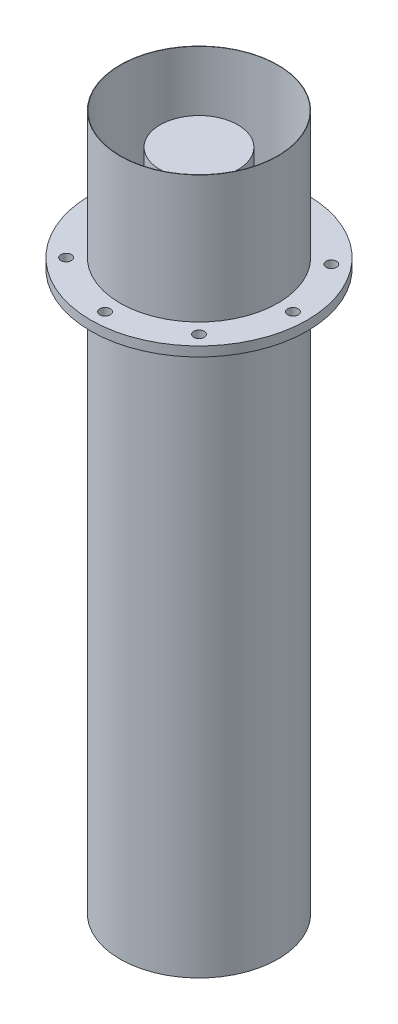
SolidWorks part; units mm, degrees
ref_plane "Alzado" through (0, 0, 0) normal (0, 0, 1) x (1, 0, 0)
ref_plane "Planta" through (0, 0, 0) normal (0, 1, 0) x (1, 0, 0)
ref_plane "Vista lateral" through (0, 0, 0) normal (1, 0, 0) x (0, 0, -1)
sketch "Croquis1" plane through (0, 0, 0) normal (0, 1, 0) x (1, 0, 0)
  circle A0 centre (0, 0) radius 24.8
  dimension "D1" = 49.6
extrude "Saliente-Extruir1" add sketch "Croquis1" along normal blind 218.4
sketch "Croquis2" plane through (0, 0, 0) normal (0, -1, 0) x (1, 0, 0)
  line L0 (0, 0) -> (0, 1.5) construction
  line L1 (0, 1.5) -> (1.4697, 1.5)
  line L2 (0, 1.5) -> (-1.4697, 1.5)
  arc A0 (-1.4697, 1.5) -> (1.4697, 1.5) centre (0, 0) ccw
  dimension "D1" = 4.2
  dimension "D2" = 1.5
extrude "Cortar-Extruir1" cut sketch "Croquis2" against normal blind 10
sketch "Croquis3" plane through (0, 218.4, 0) normal (0, 1, 0) x (1, 0, 0)
  circle A0 centre (0, 0) radius 12.2
  dimension "D1" = 24.4
extrude "Saliente-Extruir2" add sketch "Croquis3" along normal blind 30
sketch "Croquis4" plane through (0, 0, 0) normal (0, -1, 0) x (1, 0, 0)
  line L0 (0, 0) -> (0, 6.3) construction
  line L1 (0, 6.3) -> (-3.7858, 6.3) construction
  line L2 (0, 0) -> (-17.7679, 0) construction
  line L3 (-7.35, 0) -> (-3.7858, 6.3) construction
  line L5 (3.5475, 6.2184) -> (-3.6116, 6.1814)
  line L6 (-3.6116, 6.1814) -> (-7.159, -0.037)
  line L7 (-7.159, -0.037) -> (-3.5475, -6.2184)
  line L8 (-3.5475, -6.2184) -> (3.6116, -6.1814)
  line L9 (3.6116, -6.1814) -> (7.159, 0.037)
  line L10 (7.159, 0.037) -> (3.5475, 6.2184)
  circle A0 centre (0, 0) radius 7.35 construction
  circle A1 centre (0, 0) radius 6.2 construction
  dimension "D1" = 14.7
  dimension "D2" = 6.3
  dimension "D3" = 12.4
extrude "Cortar-Extruir2" cut sketch "Croquis4" against normal blind 8
sketch "Croquis5" plane through (0, 218.4, 0) normal (0, 1, 0) x (1, 0, 0)
  circle A0 centre (0, 0) radius 22.5
  circle A1 centre (0, 0) radius 24.7
  dimension "D1" = 45
  dimension "D2" = 49.4
extrude "Cortar-Extruir3" cut sketch "Croquis5" against normal blind 300
sketch "Croquis6" plane through (0, 248.4, 0) normal (0, 1, 0) x (1, 0, 0)
  circle A0 centre (0, 0) radius 25.8724
extrude "Cortar-Extruir4" cut sketch "Croquis6" against normal blind 40
sketch "Croquis7" plane through (0, 208.4, 0) normal (0, 1, 0) x (1, 0, 0)
  circle A0 centre (0, 0) radius 12.2
  circle A1 centre (0, 0) radius 30.018
  dimension "D1" = 24.4
extrude "Cortar-Extruir5" cut sketch "Croquis7" against normal blind 30
sketch "Croquis8" plane through (0, 178.4, 0) normal (0, 1, 0) x (1, 0, 0)
  line L0 (0, 0) -> (-29.5, 0) construction
  line L1 (0, 0) -> (-44.2028, 37.0906) construction
  line L2 (0, 0) -> (-37.7852, -37.7852) construction
  line L3 (0, 0) -> (0, 40.3734) construction
  circle A0 centre (0, 0) radius 34
  circle A2 centre (0, 0) radius 29.5 construction
  circle A3 centre (-22.5983, 18.9622) radius 1.65
  circle A4 centre (-29.5, 0) radius 1.65
  circle A5 centre (-20.8597, -20.8597) radius 1.65
  circle A6 centre (0, -29.5) radius 1.65
  circle A7 centre (20.8597, -20.8597) radius 1.65
  circle A8 centre (22.5983, 18.9622) radius 1.65
  circle A9 centre (29.5, 0) radius 1.65
  circle A10 centre (0, 0) radius 22.3
  dimension "D1" = 68
  dimension "D5" = 3.3
  dimension "D6" = 3.3
  dimension "D7" = 3.3
  dimension "D8" = 3.3
  dimension "D2" = 29.5
  dimension "D3" = 40
  dimension "D4" = 45
extrude "Saliente-Extruir3" add sketch "Croquis8" against normal blind 3
